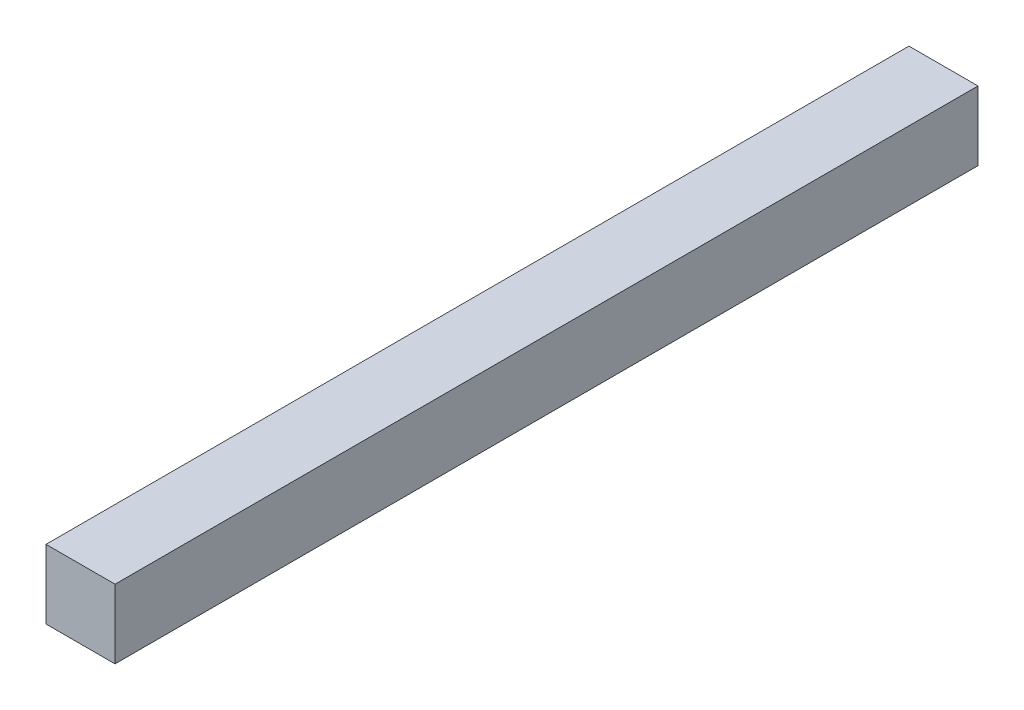
SolidWorks part; units mm, degrees
ref_plane "Front Plane" through (0, 0, 0) normal (0, 0, 1) x (1, 0, 0)
ref_plane "Top Plane" through (0, 0, 0) normal (0, 1, 0) x (1, 0, 0)
ref_plane "Right Plane" through (0, 0, 0) normal (1, 0, 0) x (0, 0, -1)
sketch "Sketch1" plane through (0, 0, 0) normal (0, 0, 1) x (1, 0, 0)
  line L1 (-10, -10) -> (10, -10)
  line L2 (-10, -10) -> (-10, 10)
  line L3 (-10, 10) -> (10, 10)
  line L4 (10, -10) -> (10, 10)
  line L5 (-10, -10) -> (10, 10) construction
  line L6 (-10, 10) -> (10, -10) construction
  point P0 (0, 0)
  dimension "D1" = 20
extrude "Boss-Extrude1" add sketch "Sketch1" along normal blind 250
